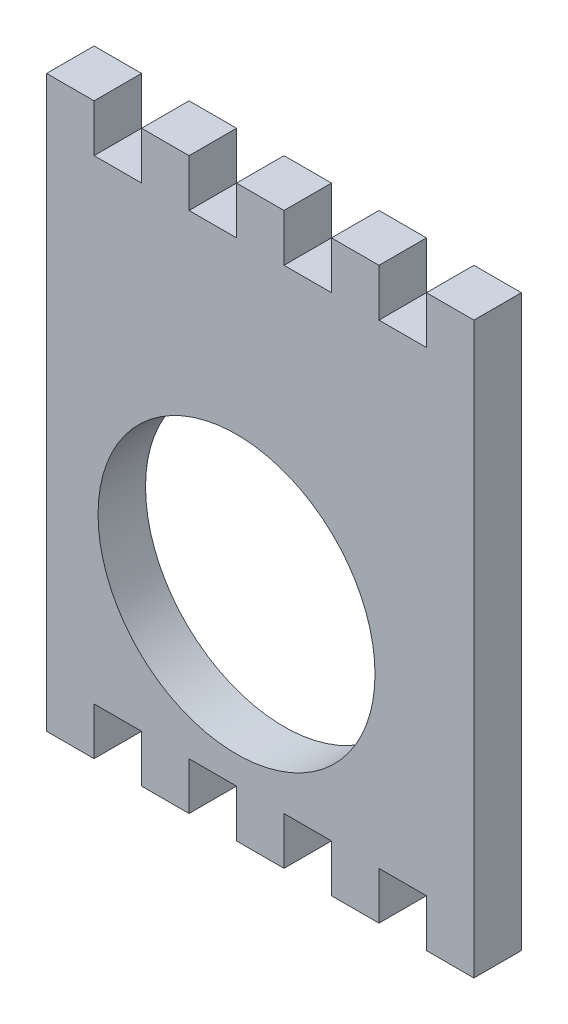
SolidWorks part; units mm, degrees
ref_plane "Front Plane" through (0, 0, 0) normal (0, 0, 1) x (1, 0, 0)
ref_plane "Top Plane" through (0, 0, 0) normal (0, 1, 0) x (1, 0, 0)
ref_plane "Right Plane" through (0, 0, 0) normal (1, 0, 0) x (0, 0, -1)
sketch "Sketch1" plane through (0, 0, 0) normal (0, 0, 1) x (1, 0, 0)
  line L0 (-20.3297, 36.6528) -> (-20.3297, 0.6528) construction
  line L1 (-33.8297, 43.3803) -> (-30.8297, 43.3803)
  line L2 (-33.8297, 43.3803) -> (-33.8297, 7.3803)
  line L3 (-33.8297, 7.3803) -> (-30.8297, 7.3803)
  line L4 (-6.8297, 43.3803) -> (-6.8297, 7.3803)
  line L5 (-33.8297, 25.3803) -> (-6.8297, 25.3803) construction
  line L6 (-24.8297, 10.3803) -> (-21.8297, 10.3803)
  line L7 (-30.8297, 10.3803) -> (-27.8297, 10.3803)
  line L8 (-30.8297, 10.3803) -> (-30.8297, 7.3803)
  line L10 (-27.8297, 10.3803) -> (-27.8297, 7.3803)
  line L11 (-24.8297, 10.3803) -> (-24.8297, 7.3803)
  line L13 (-21.8297, 10.3803) -> (-21.8297, 7.3803)
  line L14 (-15.8297, 10.3803) -> (-15.8297, 7.3803)
  line L16 (-18.8297, 10.3803) -> (-18.8297, 7.3803)
  line L17 (-15.8297, 10.3803) -> (-18.8297, 10.3803)
  line L19 (-12.8297, 10.3803) -> (-12.8297, 7.3803)
  line L20 (-9.8297, 10.3803) -> (-12.8297, 10.3803)
  line L21 (-9.8297, 10.3803) -> (-9.8297, 7.3803)
  line L22 (-9.8297, 40.3803) -> (-9.8297, 43.3803)
  line L23 (-9.8297, 40.3803) -> (-12.8297, 40.3803)
  line L24 (-12.8297, 40.3803) -> (-12.8297, 43.3803)
  line L26 (-15.8297, 40.3803) -> (-18.8297, 40.3803)
  line L27 (-18.8297, 40.3803) -> (-18.8297, 43.3803)
  line L29 (-15.8297, 40.3803) -> (-15.8297, 43.3803)
  line L30 (-24.8297, 40.3803) -> (-24.8297, 43.3803)
  line L32 (-21.8297, 40.3803) -> (-21.8297, 43.3803)
  line L33 (-24.8297, 40.3803) -> (-21.8297, 40.3803)
  line L35 (-27.8297, 40.3803) -> (-27.8297, 43.3803)
  line L36 (-30.8297, 40.3803) -> (-27.8297, 40.3803)
  line L37 (-30.8297, 40.3803) -> (-30.8297, 43.3803)
  line L38 (-27.8297, 7.3803) -> (-24.8297, 7.3803)
  line L39 (-21.8297, 7.3803) -> (-18.8297, 7.3803)
  line L40 (-15.8297, 7.3803) -> (-12.8297, 7.3803)
  line L41 (-9.8297, 7.3803) -> (-6.8297, 7.3803)
  line L42 (-27.8297, 43.3803) -> (-24.8297, 43.3803)
  line L43 (-21.8297, 43.3803) -> (-18.8297, 43.3803)
  line L44 (-15.8297, 43.3803) -> (-12.8297, 43.3803)
  line L45 (-9.8297, 43.3803) -> (-6.8297, 43.3803)
  circle A0 centre (-21.8297, 20.8803) radius 8.75
  dimension "D5" = 17.5
  dimension "D1" = 27
  dimension "D2" = 36
  dimension "D3" = 3
  dimension "D4" = 3
  dimension "D6" = 3
  dimension "D7" = 3
  dimension "D8" = 3
  dimension "D10" = 3
  dimension "D11" = 10.5
extrude "Boss-Extrude1" add sketch "Sketch1" along normal blind 3
